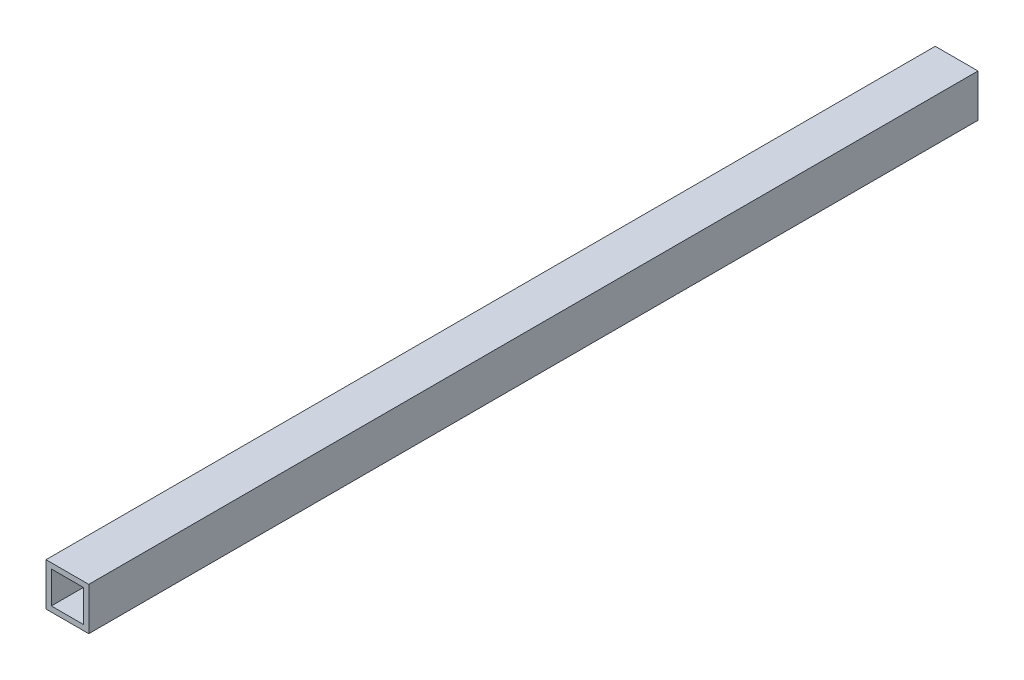
SolidWorks part; units mm, degrees
ref_plane "Front Plane" through (0, 0, 0) normal (0, 0, 1) x (1, 0, 0)
ref_plane "Top Plane" through (0, 0, 0) normal (0, 1, 0) x (1, 0, 0)
ref_plane "Right Plane" through (0, 0, 0) normal (1, 0, 0) x (0, 0, -1)
sketch "Sketch1" plane through (0, 0, 0) normal (0, 0, 1) x (1, 0, 0)
  line L0 (12.7, 0) -> (9.525, 0) construction
  line L1 (-12.7, 0) -> (12.7, 0) construction
  line L2 (0, 12.7) -> (0, -12.7)
  point P7 (0, 0)
sketch "Sketch2" plane through (0, 0, 0) normal (1, 0, 0) x (0, 0, -1)
  line L0 (264.16, 0) -> (-264.16, 0)
  point P4 (0, 0)
  dimension "Length" = 528.32
sketch "Sketch3" plane through (0, 0, 0) normal (0, 0, 1) x (1, 0, 0)
  line L0 (-12.7, 0) -> (12.7, 0) construction
  line L5 (12.7, -12.7) -> (-12.7, -12.7)
  line L6 (12.7, -12.7) -> (12.7, 12.7)
  line L11 (12.7, 12.7) -> (-12.7, 12.7)
  line L12 (-12.7, -12.7) -> (-12.7, 12.7)
  line L14 (12.7, -12.7) -> (-12.7, 12.7) construction
  line L15 (12.7, 12.7) -> (-12.7, -12.7) construction
  line L16 (9.525, -9.525) -> (-9.525, -9.525)
  line L17 (9.525, -9.525) -> (9.525, 9.525)
  line L18 (9.525, 9.525) -> (-9.525, 9.525)
  line L19 (-9.525, -9.525) -> (-9.525, 9.525)
  line L20 (9.525, -9.525) -> (-9.525, 9.525) construction
  line L21 (9.525, 9.525) -> (-9.525, -9.525) construction
  point P0 (0, 0)
  point P5 (0, 0)
  point P13 (9.525, -12.7)
  dimension "D1" = 3.175
  dimension "D3" = 25.4
  dimension "D4" = 25.4
extrude "Boss-Extrude1" add sketch "Sketch3" along normal up to vertex (264.16 mm away) and the other way up to vertex (264.16 mm away) up to point (0, 0, 264.16) other way up to point (0, 0, -264.16)
sketch "Sketch5" plane through (0, 0, 0) normal (1, 0, 0) x (0, 0, -1)
  line L0 (-264.16, 0) -> (264.16, 0) construction
  line L3 (-264.16, -12.7) -> (-264.16, 12.7) construction
  line L4 (264.16, -12.7) -> (264.16, 12.7) construction
  point P6 (-235.585, 0)
  point P7 (-226.06, 0)
  point P8 (226.06, 0)
  point P10 (235.585, 0)
  dimension "D1" = 28.575
  dimension "D2" = 38.1
  dimension "D3" = 28.575
  dimension "D4" = 38.1
equation "\"D1@Sketch3\"=\"Wall thickness@Sketch1\""
equation "\"D1@Sketch5\"=\"Width@Sketch1\"*1.125"
equation "\"D2@Sketch5\"=\"Width@Sketch1\"*1.5"
equation "\"D3@Sketch5\"=\"D1@Sketch5\""
equation "\"D4@Sketch5\"=\"D2@Sketch5\""
equation "\"D2@Sketch3\"=\"Wall Thickness@Sketch1\""
